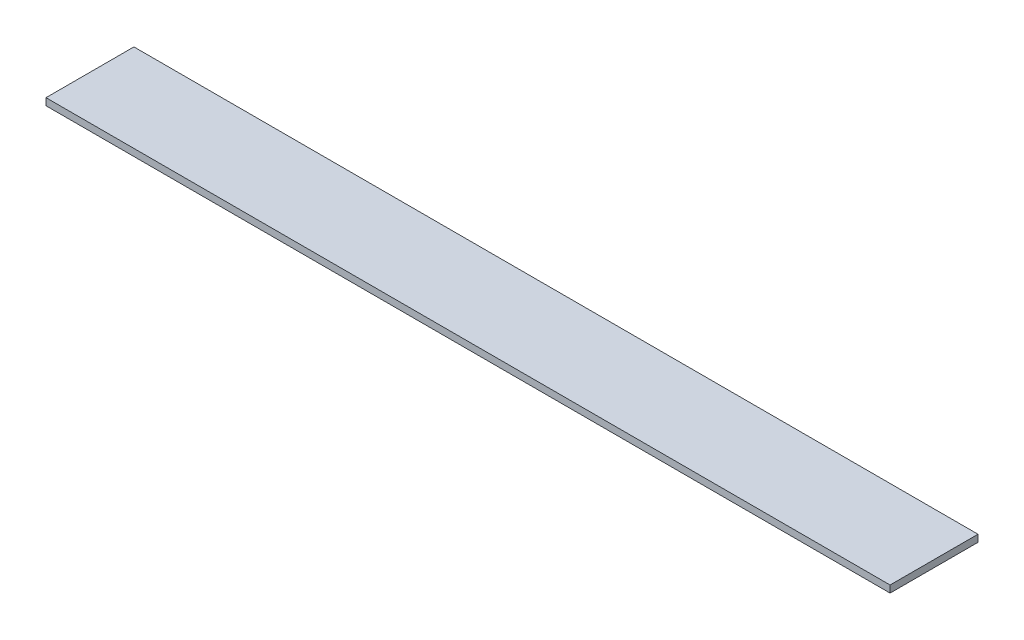
SolidWorks part; units mm, degrees
material "Natural Rubber"
ref_plane "Front Plane" through (0, 0, 0) normal (0, 0, 1) x (1, 0, 0)
ref_plane "Top Plane" through (0, 0, 0) normal (0, 1, 0) x (1, 0, 0)
ref_plane "Right Plane" through (0, 0, 0) normal (1, 0, 0) x (0, 0, -1)
sketch "Sketch1" plane through (0, 0, 0) normal (0, 1, 0) x (1, 0, 0)
  line L0 (0, 0) -> (0, 31.75)
  line L1 (0, 31.75) -> (304.8, 31.75)
  line L2 (304.8, 31.75) -> (304.8, 0)
  line L3 (304.8, 0) -> (0, 0)
  dimension "D1" = 31.75
  dimension "D2" = 304.8
extrude "Boss-Extrude1" add sketch "Sketch1" along normal blind 2.54
